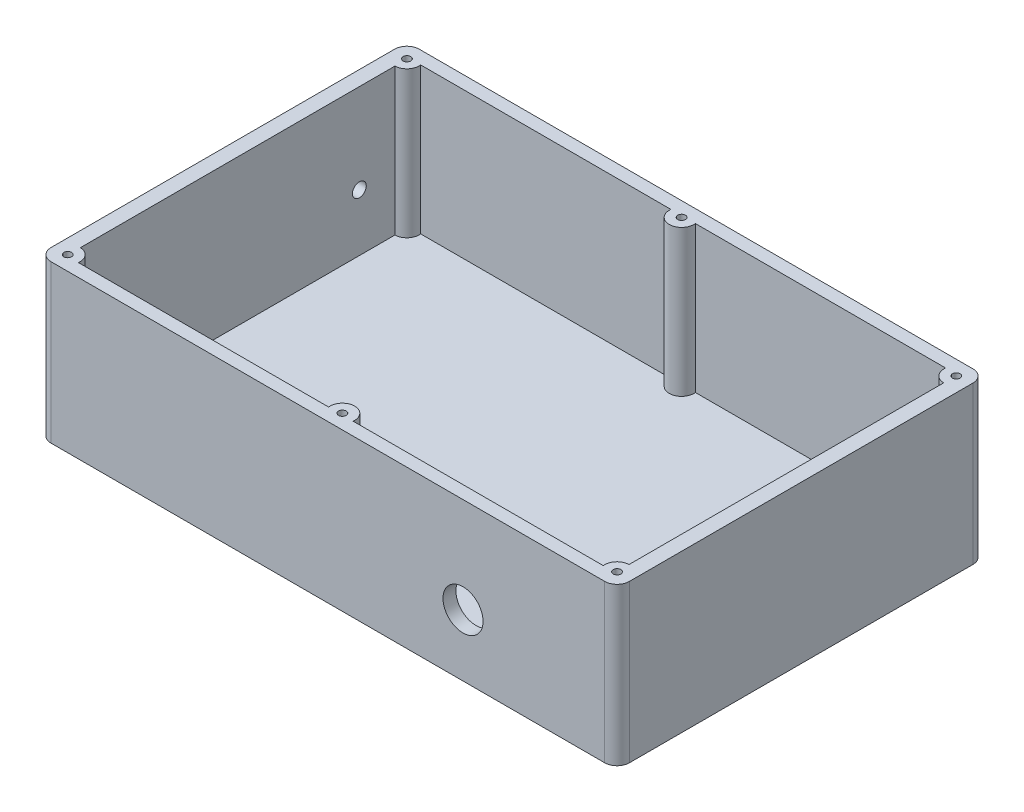
SolidWorks part; units mm, degrees
ref_plane "Front Plane" through (0, 0, 0) normal (0, 0, 1) x (1, 0, 0)
ref_plane "Top Plane" through (0, 0, 0) normal (0, 1, 0) x (1, 0, 0)
ref_plane "Right Plane" through (0, 0, 0) normal (1, 0, 0) x (0, 0, -1)
sketch "Sketch1" plane through (0, 0, 0) normal (0, 1, 0) x (1, 0, 0)
  line L1 (-89.85, 59.75) -> (89.85, 59.75)
  line L2 (-93.85, 55.75) -> (-93.85, -55.75)
  line L3 (-89.85, -59.75) -> (89.85, -59.75)
  line L4 (93.85, 55.75) -> (93.85, -55.75)
  line L5 (-93.85, 59.75) -> (93.85, -59.75) construction
  line L6 (-93.85, -59.75) -> (93.85, 59.75) construction
  arc A0 (-93.85, -55.75) -> (-89.85, -59.75) centre (-89.85, -55.75) ccw
  arc A1 (89.85, -59.75) -> (93.85, -55.75) centre (89.85, -55.75) ccw
  arc A2 (93.85, 55.75) -> (89.85, 59.75) centre (89.85, 55.75) ccw
  arc A3 (-89.85, 59.75) -> (-93.85, 55.75) centre (-89.85, 55.75) ccw
  point P0 (0, 0)
  dimension "D3" = 4
  dimension "D1" = 119.5
  dimension "D2" = 187.7
extrude "Boss-Extrude1" add sketch "Sketch1" along normal blind 51
sketch "Sketch2" plane through (0, 51, 0) normal (0, 1, 0) x (1, 0, 0)
  line L0 (89.85, 59.75) -> (-89.85, 59.75) construction
  line L1 (-87.05, 53.55) -> (87.05, 53.55) construction
  line L2 (-87.05, 53.55) -> (-87.05, -53.55) construction
  line L3 (-87.05, -53.55) -> (87.05, -53.55) construction
  line L4 (87.05, 53.55) -> (87.05, -53.55) construction
  line L5 (-87.05, 53.55) -> (87.05, -53.55) construction
  line L6 (-87.05, -53.55) -> (87.05, 53.55) construction
  line L7 (93.85, -55.75) -> (93.85, 55.75) construction
  line L8 (-93.85, 59.75) -> (-89.15, 59.75) construction
  line L9 (-89.15, 59.75) -> (-89.15, 55.05) construction
  line L10 (93.85, 59.75) -> (89.15, 59.75) construction
  line L11 (89.15, 59.75) -> (89.15, 55.05) construction
  line L12 (93.85, -59.75) -> (89.15, -59.75) construction
  line L13 (-89.85, -59.75) -> (89.85, -59.75) construction
  line L14 (89.15, -59.75) -> (89.15, -55.05) construction
  line L15 (-93.85, -59.75) -> (-89.15, -59.75) construction
  line L16 (-89.15, -59.75) -> (-89.15, -55.05) construction
  line L17 (-83.3405, -53.55) -> (-5.8095, -53.55) construction
  line L18 (87.05, -49.4295) -> (87.05, 49.4295) construction
  line L19 (5.8095, -53.55) -> (83.3405, -53.55) construction
  line L20 (-87.05, 49.4295) -> (-87.05, -49.4295) construction
  line L21 (-89.15, -55.05) -> (89.15, -55.05) construction
  line L22 (-89.15, 55.05) -> (89.15, 55.05) construction
  line L23 (5.8095, 53.55) -> (83.3405, 53.55) construction
  line L24 (-5.8095, 53.55) -> (-83.3405, 53.55) construction
  line L25 (89.85, 59.75) -> (-89.85, 59.75) construction
  line L26 (-89.05, 51.0513) -> (-89.05, -51.0513)
  line L27 (-85.1814, -55.55) -> (-3.9686, -55.55)
  line L28 (3.9686, -55.55) -> (85.1814, -55.55)
  line L29 (93.85, -55.75) -> (93.85, 55.75) construction
  line L30 (-89.85, -59.75) -> (89.85, -59.75) construction
  line L31 (-93.85, 55.75) -> (-93.85, -55.75) construction
  line L32 (89.05, -51.0513) -> (89.05, 51.0513)
  line L33 (3.9686, 55.55) -> (85.1814, 55.55)
  line L34 (-3.9686, 55.55) -> (-85.1814, 55.55)
  arc A0 (83.3405, 53.55) -> (87.05, 49.4295) centre (89.15, 55.05) ccw construction
  arc A1 (-83.3405, 53.55) -> (-87.05, 49.4295) centre (-89.15, 55.05) cw construction
  arc A2 (-83.3405, -53.55) -> (-87.05, -49.4295) centre (-89.15, -55.05) ccw construction
  arc A3 (83.3405, -53.55) -> (87.05, -49.4295) centre (89.15, -55.05) cw construction
  arc A4 (-5.8095, 53.55) -> (5.8095, 53.55) centre (0, 55.05) ccw construction
  arc A5 (-5.8095, -53.55) -> (5.8095, -53.55) centre (0, -55.05) cw construction
  arc A6 (-85.1814, -55.55) -> (-89.05, -51.0513) centre (-89.15, -55.05) ccw
  arc A7 (-3.9686, -55.55) -> (3.9686, -55.55) centre (0, -55.05) cw
  arc A8 (85.1814, -55.55) -> (89.05, -51.0513) centre (89.15, -55.05) cw
  arc A9 (85.1814, 55.55) -> (89.05, 51.0513) centre (89.15, 55.05) ccw
  arc A10 (-3.9686, 55.55) -> (3.9686, 55.55) centre (0, 55.05) ccw
  arc A11 (-85.1814, 55.55) -> (-89.05, 51.0513) centre (-89.15, 55.05) cw
  point P0 (0, 0)
  point P36 (0, 55.05)
  point P37 (0, -55.05)
  dimension "D4" = 6
  dimension "D1" = 6.2
  dimension "D2" = 6.8
  dimension "D3" = 4.7
  dimension "D5" = 2
extrude "Cut-Extrude1" cut sketch "Sketch2" against normal blind 47.5
hole_wizard "M3x0.5 Tapped Hole1" positions "Sketch5" profile "Sketch4" tap size "M3x0.5" standard "ANSI Metric"
sketch "Sketch5" plane through (0, 51, 0) normal (0, 1, 0) x (1, 0, 0)
  point P0 (-89.15, 55.05)
  point P3 (-89.15, -55.05)
  point P6 (89.15, -55.05)
  point P9 (89.15, 55.05)
  point P13 (0, -55.05)
  point P16 (0, 55.05)
sketch "Sketch4" plane through (-89.15, 51, -55.05) normal (1, 0, 0) x (0, 0, 1)
  line L0 (0, 0) -> (0, 8.2511)
  line L1 (0, 8.2511) -> (1.25, 7.5)
  line L2 (1.25, 7.5) -> (1.25, 0)
  line L5 (1.25, 0) -> (0, 0)
  line L10 (0, 8.2511) -> (-1.25, 7.5) construction
  line L11 (0, -6.35) -> (0, 107.95) construction
  dimension "Tap Drill Dia." = 2.5
  dimension "Tap Drill Depth" = 7.5
  dimension "Drill Angle" = 118
sketch "Sketch6" plane through (0, 51, 0) normal (0, 1, 0) x (1, 0, 0)
  line L0 (-89.85, -59.75) -> (89.85, -59.75) construction
  line L1 (-102.5, 59.75) -> (102.5, 59.75)
  line L2 (-102.5, 59.75) -> (-102.5, -59.75)
  line L3 (-102.5, -59.75) -> (102.5, -59.75)
  line L4 (102.5, 59.75) -> (102.5, -59.75)
  line L5 (-102.5, 59.75) -> (102.5, -59.75) construction
  line L6 (-102.5, -59.75) -> (102.5, 59.75) construction
  point P0 (0, 0)
  dimension "D1" = 205
extrude "Cut-Extrude2" [suppressed] cut sketch "Sketch6" against normal blind 18
sketch "Sketch7" [suppressed] plane through (0, 33, 0) normal (0, 1, 0) x (1, 0, 0)
  line L0 (102.5, 72.35) -> (42.5, 72.35)
  line L1 (102.5, 72.35) -> (-102.5, 72.35) construction
  line L2 (42.5, 72.35) -> (42.5, 52.35)
  line L3 (42.5, 52.35) -> (102.5, 52.35)
  line L4 (102.5, 52.35) -> (102.5, 72.35)
  dimension "D1" = 60
  dimension "D2" = 20
extrude "Cut-Extrude3" [suppressed] cut sketch "Sketch7" against normal blind 4
sketch "Sketch8" plane through (93.85, 0, 0) normal (1, 0, 0) x (0, 0, -1)
  line L0 (0, 51) -> (0, 16) construction
  line L1 (-55.75, 51) -> (55.75, 51) construction
  line L2 (0, 16) -> (35, 16) construction
  line L3 (0, 16) -> (-35, 16) construction
  line L4 (29, 21) -> (41, 21)
  line L5 (26, 18) -> (26, 14)
  line L6 (29, 11) -> (41, 11)
  line L7 (44, 18) -> (44, 14)
  line L8 (26, 21) -> (44, 11) construction
  line L9 (26, 11) -> (44, 21) construction
  line L10 (-35, 16) -> (-24, 16) construction
  line L11 (-35, 16) -> (-46, 16) construction
  line L12 (35, 16) -> (22.5, 16) construction
  line L13 (35, 16) -> (47.5, 16) construction
  arc A0 (26, 14) -> (29, 11) centre (29, 14) ccw
  arc A1 (41, 11) -> (44, 14) centre (41, 14) ccw
  arc A2 (44, 18) -> (41, 21) centre (41, 18) ccw
  arc A3 (29, 21) -> (26, 18) centre (29, 18) ccw
  circle A4 centre (-35, 16) radius 8
  dimension "D1" = 3
  dimension "D7" = 16
  dimension "D2" = 35
  dimension "D3" = 35
  dimension "D4" = 18
  dimension "D5" = 10
  dimension "D6" = 22
  dimension "D8" = 35
  dimension "D9" = 25
extrude "Cut-Extrude4" [suppressed] cut sketch "Sketch8" against normal up to next
hole_wizard "M3 Clearance Hole1" [suppressed] positions "Sketch10" profile "Sketch9" hole size "M3" standard "ANSI Metric"
sketch "Sketch10" plane through (93.85, 0, 0) normal (1, 0, 0) x (0, 0, -1)
  point P0 (-46, 16)
  point P3 (-24, 16)
  point P7 (22.5, 16)
  point P10 (47.5, 16)
sketch "Sketch9" plane through (93.85, 16, 46) normal (0, 1, 0) x (0, 0, -1)
  line L0 (0, 0) -> (0, 4.8)
  line L1 (0, 4.8) -> (1.7, 4.8)
  line L2 (1.7, 4.8) -> (1.7, 0)
  line L5 (1.7, 0) -> (0, 0)
  line L11 (0, -6.35) -> (0, 107.95) construction
  dimension "Thru Hole Dia." = 3.4
  dimension "Thru Hole Depth" = 4.8
hole_wizard "M4 Clearance Hole2" positions "Sketch15" profile "Sketch14" hole size "M4" standard "ANSI Metric"
sketch "Sketch15" plane through (-93.85, 0, 0) normal (-1, 0, 0) x (0, 0, 1)
  line L0 (0, 0) -> (0, 22)
  line L1 (0, 22) -> (-39.5, 22) construction
  line L5 (0, 22) -> (39.5, 22) construction
  point P5 (-39.5, 22)
  point P14 (39.5, 22)
  point P25 (8.1484, 22)
  point P26 (0, 0)
  point P27 (0, 0)
  point P28 (0, 0)
  dimension "D1" = 79
  dimension "D2" = 22
sketch "Sketch14" plane through (-93.85, 22, -39.5) normal (0, 1, 0) x (0, 0, 1)
  line L0 (0, 0) -> (0, 4.8)
  line L1 (0, 4.8) -> (2.25, 4.8)
  line L2 (2.25, 4.8) -> (2.25, 0)
  line L5 (2.25, 0) -> (0, 0)
  line L11 (0, -6.35) -> (0, 107.95) construction
  dimension "Thru Hole Dia." = 4.5
  dimension "Thru Hole Depth" = 4.8
hole_wizard "M6 Clearance Hole1" [suppressed] positions "Sketch17" profile "Sketch16" hole size "M6" standard "ANSI Metric"
sketch "Sketch17" plane through (0, 0, 59.75) normal (0, 0, 1) x (1, 0, 0)
  line L0 (0, 0) -> (0, 22)
  line L1 (0, 22) -> (-90, 22)
  point P5 (-90, 22)
  dimension "D1" = 22
  dimension "D2" = 90
sketch "Sketch16" plane through (-90, 22, 59.75) normal (1, 0, 0) x (0, -1, 0)
  line L0 (0, 0) -> (0, 43.25)
  line L1 (0, 43.25) -> (3.3, 43.25)
  line L2 (3.3, 43.25) -> (3.3, 0)
  line L5 (3.3, 0) -> (0, 0)
  line L11 (0, -6.35) -> (0, 107.95) construction
  dimension "Thru Hole Dia." = 6.6
  dimension "Thru Hole Depth" = 43.25
sketch "Sketch18" plane through (0, 0, 59.75) normal (0, 0, 1) x (1, 0, 0)
  line L0 (93.85, 0) -> (93.85, 20) construction
  line L1 (93.85, 51) -> (93.85, 0) construction
  line L2 (93.85, 20) -> (43.85, 20) construction
  line L3 (43.85, 20) -> (-33.85, 20) construction
  line L4 (-33.85, 20) -> (-53.85, 20) construction
  line L5 (-93.85, 51) -> (-93.85, 0) construction
  dimension "D1" = 20
  dimension "D2" = 50
  dimension "D3" = 20
  dimension "D4" = 40
hole_wizard "Ø13.0 (13) Diameter Hole1" positions "Sketch19" profile "Sketch20" hole size "Ø13.0" standard "ANSI Metric"
sketch "Sketch19" plane through (0, 0, 59.75) normal (0, 0, 1) x (1, 0, 0)
  point P0 (43.85, 20)
sketch "Sketch20" plane through (43.85, 20, 59.75) normal (1, 0, 0) x (0, -1, 0)
  line L0 (0, 0) -> (0, 4.2)
  line L1 (0, 4.2) -> (6.5, 4.2)
  line L2 (6.5, 4.2) -> (6.5, 0)
  line L5 (6.5, 0) -> (0, 0)
  line L11 (0, -6.35) -> (0, 107.95) construction
  dimension "Thru Hole Dia." = 13
  dimension "Thru Hole Depth" = 4.2
